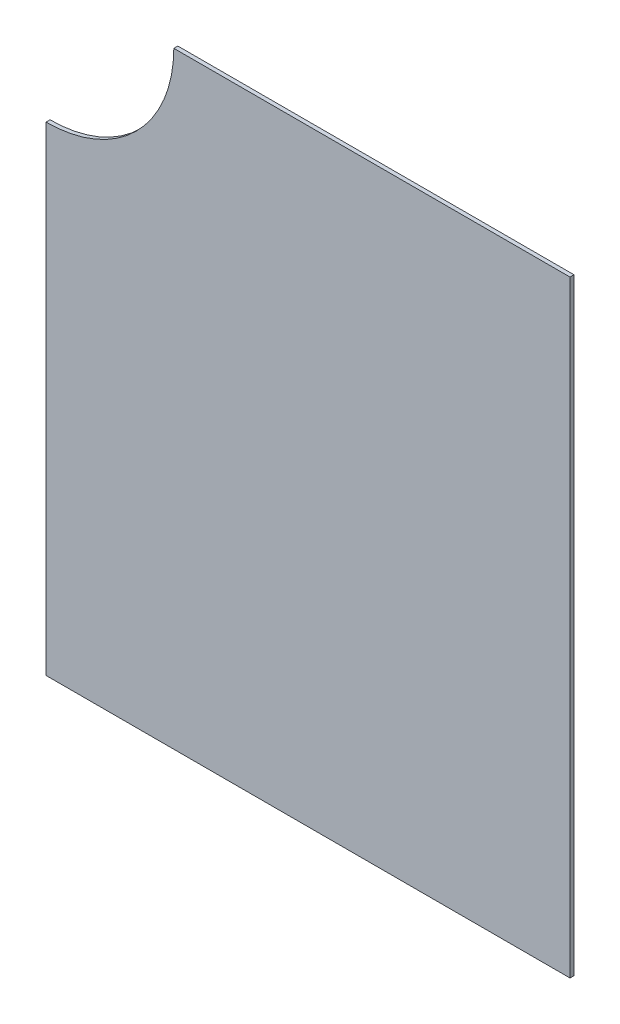
SolidWorks part; units mm, degrees
material "Acrylic (Medium-high impact)"
ref_plane "Front Plane" through (0, 0, 0) normal (0, 0, 1) x (1, 0, 0)
ref_plane "Top Plane" through (0, 0, 0) normal (0, 1, 0) x (1, 0, 0)
ref_plane "Right Plane" through (0, 0, 0) normal (1, 0, 0) x (0, 0, -1)
sketch "Sketch2" plane through (0, 0, 0) normal (0, 0, 1) x (1, 0, 0)
  line L0 (50.8, 0) -> (182.88, 0)
  line L2 (50.8, 0) -> (182.88, 0)
  line L3 (0, -50.8) -> (0, -241.3)
  line L4 (0, -241.3) -> (182.88, -241.3)
  line L5 (182.88, 0) -> (182.88, -241.3) construction
  line L6 (0, -50.8) -> (0, 0) construction
  line L8 (182.88, 0) -> (208.28, 0)
  line L9 (182.88, 0) -> (182.88, -241.3)
  line L10 (182.88, -241.3) -> (208.28, -241.3)
  line L11 (208.28, 0) -> (208.28, -241.3)
  arc A0 (0, -50.8) -> (50.8, 0) centre (0, 0) ccw
  dimension "D1" = 50.8
  dimension "D2" = 241.3
  dimension "D3" = 182.88
  dimension "D4" = 190.5
  dimension "D5" = 25.4
extrude "Boss-Extrude1" add sketch "Sketch2" along normal mid plane 1.5875 contours A0 L3 L4 L9 L0 | L11 L8 L9 L10
sketch "Sketch4" plane through (0, 0, 0.7937) normal (0, 0, 1) x (1, 0, 0)
  line L0 (182.88, -120.65) -> (0, -120.65) construction
  line L1 (182.88, 0) -> (182.88, -241.3) construction
  line L2 (0, -50.8) -> (0, -241.3) construction
  line L3 (43.18, 0) -> (43.18, -241.3)
  line L4 (50.8, 0) -> (182.88, 0) construction
  line L5 (0, -241.3) -> (182.88, -241.3) construction
  dimension "D1" = 139.7
